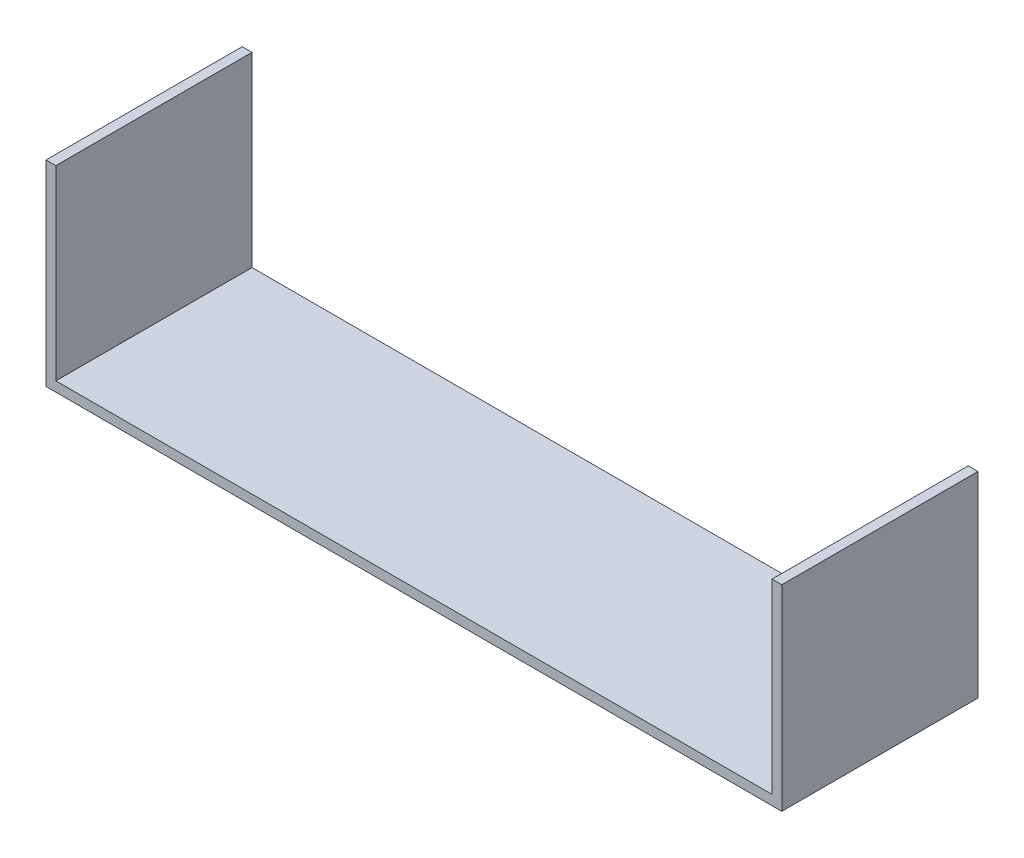
SolidWorks part; units mm, degrees
ref_plane "Front Plane" through (0, 0, 0) normal (0, 0, 1) x (1, 0, 0)
ref_plane "Top Plane" through (0, 0, 0) normal (0, 1, 0) x (1, 0, 0)
ref_plane "Right Plane" through (0, 0, 0) normal (1, 0, 0) x (0, 0, -1)
sketch "Sketch1" plane through (0, 0, 0) normal (0, 0, 1) x (1, 0, 0)
  line L0 (-75, 40) -> (-75, 0)
  line L1 (-75, 0) -> (75, 0)
  line L2 (75, 0) -> (75, 40)
  line L3 (75, 40) -> (-75, 40) construction
  line L4 (-73, 40) -> (-73, 2)
  line L5 (-73, 2) -> (73, 2)
  line L6 (73, 2) -> (73, 40)
  line L7 (-75, 40) -> (-73, 40)
  line L8 (73, 40) -> (75, 40)
  dimension "D2" = 150
  dimension "D3" = 40
  dimension "D1" = 2
extrude "Boss-Extrude1" add sketch "Sketch1" along normal blind 40
